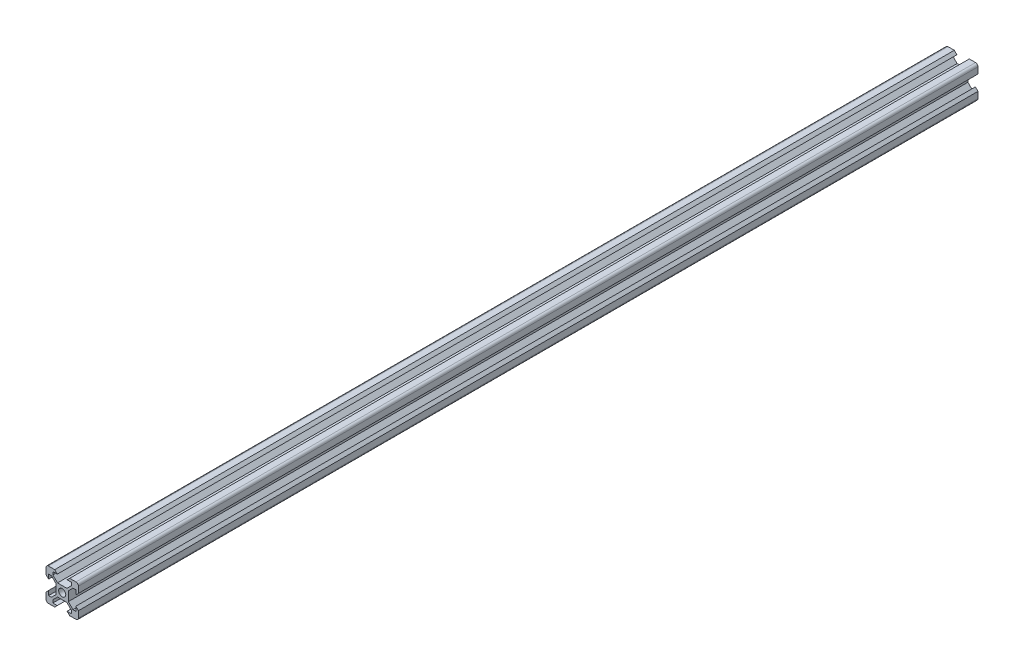
SolidWorks part; units mm, degrees
ref_plane "Front Plane" through (0, 0, 0) normal (0, 0, 1) x (1, 0, 0)
ref_plane "Top Plane" through (0, 0, 0) normal (0, 1, 0) x (1, 0, 0)
ref_plane "Right Plane" through (0, 0, 0) normal (1, 0, 0) x (0, 0, -1)
sketch "Sketch1" plane through (0, 0, 0) normal (0, 0, 1) x (1, 0, 0)
  line L0 (-5.7847, 7.544) -> (-11.512, 13.2713)
  line L1 (-7.544, 7.544) -> (7.544, 7.544)
  line L2 (-7.544, 7.544) -> (-7.544, -7.544)
  line L3 (-7.544, -7.544) -> (7.544, -7.544)
  line L4 (7.544, 7.544) -> (7.544, -7.544)
  line L5 (-7.544, 7.544) -> (7.544, -7.544) construction
  line L6 (-7.544, -7.544) -> (7.544, 7.544) construction
  line L7 (-11.512, 13.2713) -> (-11.512, 16.8)
  line L8 (-11.512, 16.8) -> (-6.052, 16.8)
  line L9 (-6.052, 16.8) -> (-9.252, 20)
  line L10 (-9.252, 20) -> (-17, 20)
  line L11 (-20, 17) -> (-20, 9.252)
  line L12 (-20, 9.252) -> (-16.8, 6.052)
  line L13 (-16.8, 6.052) -> (-16.8, 11.512)
  line L14 (-16.8, 11.512) -> (-13.2713, 11.512)
  line L15 (-13.2713, 11.512) -> (-7.544, 5.7847)
  line L16 (-19.1213, 19.1213) -> (0, 0) construction
  line L17 (13.2713, 11.512) -> (16.8, 11.512)
  line L18 (20, 9.252) -> (20, 17)
  line L19 (17, 20) -> (9.252, 20)
  line L20 (9.252, 20) -> (6.052, 16.8)
  line L21 (6.052, 16.8) -> (11.512, 16.8)
  line L22 (11.512, 16.8) -> (11.512, 13.2713)
  line L23 (11.512, 13.2713) -> (5.7847, 7.544)
  line L24 (7.544, 5.7847) -> (13.2713, 11.512)
  line L25 (16.8, 11.512) -> (16.8, 6.052)
  line L26 (16.8, 6.052) -> (20, 9.252)
  line L27 (19.1213, 19.1213) -> (0, 0) construction
  line L28 (11.512, -13.2713) -> (11.512, -16.8)
  line L29 (9.252, -20) -> (17, -20)
  line L30 (20, -17) -> (20, -9.252)
  line L31 (20, -9.252) -> (16.8, -6.052)
  line L32 (16.8, -6.052) -> (16.8, -11.512)
  line L33 (16.8, -11.512) -> (13.2713, -11.512)
  line L34 (13.2713, -11.512) -> (7.544, -5.7847)
  line L35 (5.7847, -7.544) -> (11.512, -13.2713)
  line L36 (11.512, -16.8) -> (6.052, -16.8)
  line L37 (6.052, -16.8) -> (9.252, -20)
  line L38 (19.1213, -19.1213) -> (0, 0) construction
  line L39 (-13.2713, -11.512) -> (-16.8, -11.512)
  line L40 (-20, -9.252) -> (-20, -17)
  line L41 (-17, -20) -> (-9.252, -20)
  line L42 (-9.252, -20) -> (-6.052, -16.8)
  line L43 (-6.052, -16.8) -> (-11.512, -16.8)
  line L44 (-11.512, -16.8) -> (-11.512, -13.2713)
  line L45 (-11.512, -13.2713) -> (-5.7847, -7.544)
  line L46 (-7.544, -5.7847) -> (-13.2713, -11.512)
  line L47 (-16.8, -11.512) -> (-16.8, -6.052)
  line L48 (-16.8, -6.052) -> (-20, -9.252)
  line L49 (-19.1213, -19.1213) -> (0, 0) construction
  circle A0 centre (0, 0) radius 4.4
  arc A1 (-17, 20) -> (-20, 17) centre (-17, 17) ccw
  arc A2 (20, 17) -> (17, 20) centre (17, 17) ccw
  arc A3 (17, -20) -> (20, -17) centre (17, -17) ccw
  arc A4 (-20, -17) -> (-17, -20) centre (-17, -17) ccw
  point P66 (0, 0)
  dimension "D1" = 8.8
  dimension "D8" = 3
  dimension "D2" = 15.088
  dimension "D3" = 2.488
  dimension "D4" = 8.488
  dimension "D5" = 3.2
  dimension "D6" = 20
  dimension "D7" = 15.2
  dimension "D9" = 4
extrude "Boss-Extrude1" add sketch "Sketch1" along normal mid plane 1110 contours L10 A1 L11 L12 L13 L14 L15 L2 L1 L0 L7 L8 L9 | L18 A2 L19 L20 L21 L22 L23 L1 L4 L24 L17 L25 L26 | L40 A4 L41 L42 L43 L44 L45 L3 L2 L46 L39 L47 L48 | L29 A3 L30 L31 L32 L33 L34 L4 L3 L35 L28 L36 L37 | L4 L1 L2 L3 A0
equation "\"longitud\"= 800"
